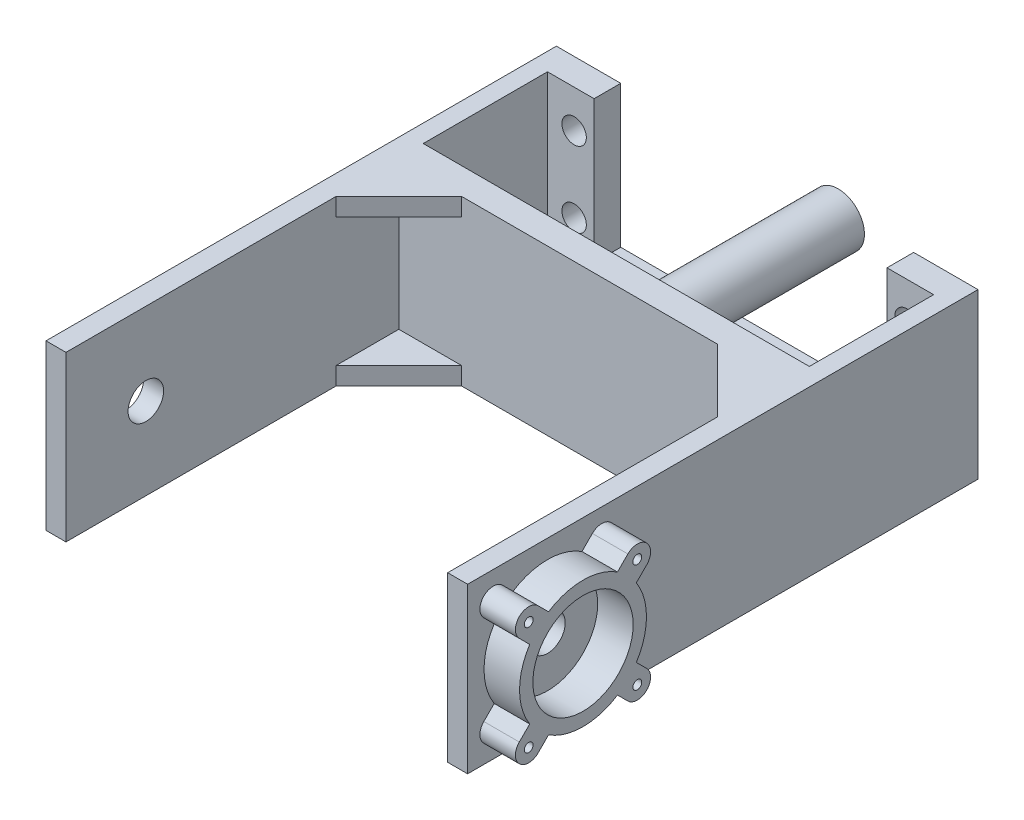
SolidWorks part; units mm, degrees
material "ABS"
ref_plane "Front Plane" through (0, 0, 0) normal (0, 0, 1) x (1, 0, 0)
ref_plane "Top Plane" through (0, 0, 0) normal (0, 1, 0) x (1, 0, 0)
ref_plane "Right Plane" through (0, 0, 0) normal (1, 0, 0) x (0, 0, -1)
sketch "Sketch1" plane through (0, 0, 0) normal (0, 1, 0) x (1, 0, 0)
  line L1 (-47.5, 20) -> (47.5, 20)
  line L2 (-47.5, 20) -> (-47.5, -20)
  line L3 (-47.5, -20) -> (47.5, -20)
  line L4 (47.5, 20) -> (47.5, -20)
  line L5 (-47.5, 20) -> (47.5, -20) construction
  line L6 (-47.5, -20) -> (47.5, 20) construction
  point P0 (0, 0)
  dimension "D1" = 95
  dimension "D2" = 40
extrude "Boss-Extrude1" add sketch "Sketch1" along normal blind 5
sketch "Sketch2" plane through (0, 5, 0) normal (0, 1, 0) x (1, 0, 0)
  line L0 (0, 20) -> (0, -20) construction
  line L1 (-47.5, -20) -> (47.5, -20) construction
  line L2 (-33, 20) -> (-33, -20) construction
  line L3 (47.5, 20) -> (-47.5, 20) construction
  line L4 (-47.5, 20) -> (-47.5, -20) construction
  line L5 (-33, 20) -> (-47.5, 20)
  line L6 (-33, 20) -> (-33, 14)
  line L7 (-33, 14) -> (-47.5, 14)
  line L8 (-47.5, 20) -> (-47.5, 14)
  line L9 (33, 14) -> (47.5, 14)
  line L10 (47.5, 20) -> (47.5, 14)
  line L11 (33, 20) -> (47.5, 20)
  line L12 (33, 20) -> (33, 14)
  point P6 (0, 0)
  dimension "D1" = 33
  dimension "D2" = 6
extrude "Boss-Extrude2" add sketch "Sketch2" along normal blind 32
sketch "Sketch3" plane through (0, 37, 0) normal (0, 1, 0) x (1, 0, 0)
  line L1 (-47.5, 20) -> (47.5, 20)
  line L2 (-47.5, 20) -> (-47.5, 14)
  line L3 (-47.5, 14) -> (47.5, 14)
  line L4 (47.5, 20) -> (47.5, 14)
extrude "Boss-Extrude3" [suppressed] add sketch "Sketch3" against normal blind 6
sketch "Sketch4" plane through (0, 0, -20) normal (0, 0, -1) x (-1, 0, 0)
  line L0 (0, 0) -> (0, 43) construction
  line L2 (-33, 5) -> (33, 5) construction
  circle A0 centre (37.5, 11.5) radius 2.75
  circle A1 centre (37.5, 28.5) radius 2.75
  circle A2 centre (-37.5, 28.5) radius 2.75
  circle A3 centre (-37.5, 11.5) radius 2.75
  dimension "D1" = 5.5
  dimension "D4" = 5.5
  dimension "D2" = 37.5
  dimension "D3" = 17
extrude "Cut-Extrude1" cut sketch "Sketch4" against normal blind 6
sketch "Sketch6" plane through (0, 5, 0) normal (0, 1, 0) x (1, 0, 0)
  line L0 (-47.5, -20) -> (47.5, -20) construction
  line L2 (0, 0) -> (0, -20) construction
  circle A0 centre (-38, 0) radius 2.7
  circle A1 centre (38, 0) radius 2.7
  dimension "D1" = 20
  dimension "D2" = 76
extrude "Cut-Extrude2" [suppressed] cut sketch "Sketch6" against normal blind 6
sketch "Sketch7" plane through (-47.5, 0, 0) normal (-1, 0, 0) x (0, 0, 1)
  line L0 (20, 5) -> (-14, 37)
  line L1 (-14, 37) -> (-14, 5)
  line L2 (-14, 5) -> (20, 5)
extrude "Boss-Extrude4" [suppressed] add sketch "Sketch7" against normal blind 4
mirror "Mirror1" [suppressed] about plane through (0, 0, 0) normal (1, 0, 0)
sketch "Sketch9" [suppressed] plane through (0, 5, 0) normal (0, 1, 0) x (1, 0, 0)
  line L0 (47.5, -20) -> (47.5, 14) construction
  line L1 (-47.5, -20) -> (47.5, -20)
  line L2 (-47.5, -20) -> (-47.5, -14)
  line L3 (-47.5, -14) -> (47.5, -14)
  line L4 (47.5, -20) -> (47.5, -14)
  dimension "D1" = 6
sketch "Sketch10" plane through (0, 5, 0) normal (0, 1, 0) x (1, 0, 0)
  line L0 (47.5, -20) -> (47.5, 14) construction
  line L1 (-47.5, -20) -> (47.5, -20)
  line L2 (-47.5, -20) -> (-47.5, -14)
  line L3 (-43.5, -14) -> (43.5, -14)
  line L4 (47.5, -20) -> (47.5, -19)
  line L5 (-47.5, 14) -> (-33, 14) construction
  line L6 (-47.5, -20) -> (-43.5, -20)
  line L7 (-47.5, -20) -> (-47.5, 14)
  line L8 (-47.5, 14) -> (-43.5, 14)
  line L9 (-43.5, -14) -> (-43.5, 14)
  line L10 (33, 14) -> (47.5, 14) construction
  line L11 (47.5, -20) -> (43.5, -20)
  line L12 (47.5, -20) -> (47.5, 14)
  line L13 (47.5, 14) -> (43.5, 14)
  line L14 (43.5, -14) -> (43.5, 14)
  line M12 (47.5, 14) -> (33, 14)
  line M16 (-33, 14) -> (-47.5, 14)
  line M17 (-47.5, 14) -> (-47.5, -20)
  line M18 (-47.5, -20) -> (47.5, -20)
  line M19 (47.5, -20) -> (47.5, 14)
  dimension "D1" = 6
  dimension "D2" = 4
  dimension "D3" = 4
extrude "Boss-Extrude5" add sketch "Sketch10" along normal blind 32 contours L14 L3 L9 L1 M16 M17 M18 M19 M12
sketch "Sketch11" plane through (0, 0, 20) normal (0, 0, 1) x (1, 0, 0)
  line L0 (0, 0) -> (0, 37) construction
  line L1 (-47.5, 37) -> (47.5, 37) construction
  line L2 (-47.5, 0) -> (47.5, 0) construction
  line L6 (-43, 37) -> (-43, 0)
  line L7 (-43, 0) -> (-47.5, 0)
  line L8 (-47.5, 0) -> (-47.5, 37)
  line L9 (-47.5, 37) -> (-43, 37)
  line L10 (47.5, 0) -> (47.5, 37)
  line L11 (43, 0) -> (47.5, 0)
  line L12 (43, 37) -> (43, 0)
  line L13 (47.5, 37) -> (43, 37)
  dimension "D1" = 43
  dimension "D2" = 4.5
extrude "Boss-Extrude6" add sketch "Sketch11" along normal blind 75
sketch "Sketch12" plane through (-47.5, 0, 0) normal (-1, 0, 0) x (0, 0, 1)
  line L0 (95, 37) -> (95, 0) construction
  circle A0 centre (77, 18.5) radius 4
  dimension "D1" = 18
extrude "Cut-Extrude3" cut sketch "Sketch12" against normal blind 110
sketch "Sketch14" plane through (47.5, 0, 0) normal (1, 0, 0) x (0, 0, -1)
  line L2 (-51.8884, 4.1457) -> (-51.7374, 6.3175)
  line L3 (-47.6457, 8.3884) -> (-50.0959, 10.5765)
  line L6 (-76.3543, 8.3884) -> (-58.0271, -2.1553)
  line L7 (-72.1116, 4.1457) -> (-83.6295, -8.7518)
  line L10 (-72.1116, 32.8543) -> (-56.5863, 37.7326)
  line L11 (-76.3543, 28.6116) -> (-91.7462, 42.3571)
  line L14 (-47.6457, 28.6116) -> (-50.05, 26.266)
  line L15 (-51.8884, 32.8543) -> (-52.5061, 32.1625)
  circle A2 centre (-77, 18.5) radius 25.0466
  arc A3 (-91.7462, 42.3571) -> (-58.0271, -2.1553) centre (-77, 18.5) ccw
  arc A6 (-51.8884, 4.1457) -> (-47.8982, 8.6138) centre (-49.7671, 6.2671) ccw
  circle A7 centre (-49.7671, 6.2671) radius 1
  arc A10 (-76.3543, 8.3884) -> (-71.8862, 4.3982) centre (-74.2329, 6.2671) ccw
  circle A11 centre (-74.2329, 6.2671) radius 1
  arc A14 (-72.1116, 32.8543) -> (-76.1018, 28.3862) centre (-74.2329, 30.7329) ccw
  circle A15 centre (-74.2329, 30.7329) radius 1
  arc A18 (-47.6457, 28.6116) -> (-52.1138, 32.6018) centre (-49.7671, 30.7329) ccw
  circle A19 centre (-49.7671, 30.7329) radius 1
  circle A20 centre (-77, 18.5) radius 28.0466 construction
  arc A21 (-83.6295, -8.7518) -> (-51.7374, 6.3175) centre (-77, 18.5) ccw
  arc A22 (-50.0959, 10.5765) -> (-50.05, 26.266) centre (-77, 18.5) ccw
  arc A23 (-52.5061, 32.1625) -> (-56.5863, 37.7326) centre (-77, 18.5) ccw
  point P64 (-62, 18.5)
  dimension "D1" = 3
extrude "Boss-Extrude8" [suppressed] add sketch "Sketch14" along normal blind 8 contours L15 A23 L10 A14 L11 A3 L6 A10 L7 A21 L2 A6 L3 A22 L14 A18 A2 A7 A11 A15 A19
sketch "Sketch15" plane through (0, 37, 0) normal (0, 1, 0) x (1, 0, 0)
  line L0 (28.8579, -20) -> (43, -34.1421)
  line L1 (-43, -20) -> (43, -20) construction
  line L2 (43, -95) -> (43, -20) construction
  line L3 (0, 0) -> (0, -25.5678) construction
  line L4 (28.8579, -20) -> (43, -20)
  line L5 (43, -20) -> (43, -34.1421)
  line L6 (-28.8579, -20) -> (-43, -20)
  line L7 (-28.8579, -20) -> (-43, -34.1421)
  line L8 (-43, -20) -> (-43, -34.1421)
  dimension "D1" = 20
  dimension "D2" = 45
extrude "Boss-Extrude9" add sketch "Sketch15" against normal blind 4
ref_plane "Plane1" through (0, 18.5, 0) normal (0, 1, 0) x (1, 0, 0)
mirror "Mirror2" about plane through (0, 18.5, 0) normal (0, 1, 0) of "Boss-Extrude9"
sketch "Sketch16" plane through (47.5, 0, 0) normal (1, 0, 0) x (0, 0, -1)
  line L0 (-77, 37) -> (-77, 0) construction
  line L1 (-95, 37) -> (20, 37) construction
  line L2 (-66.8884, 4.1457) -> (-69.2347, 6.4921)
  line L3 (-62.6457, 8.3884) -> (-64.9921, 10.7347)
  line L4 (-95, 0) -> (20, 0) construction
  line L5 (-95, 0) -> (-95, 37) construction
  line L6 (-91.3543, 8.3884) -> (-89.0079, 10.7347)
  line L7 (-87.1116, 4.1457) -> (-84.7653, 6.4921)
  line L8 (-95, 18.5) -> (-53.5634, 18.5) construction
  line L10 (-87.1116, 32.8543) -> (-84.7653, 30.5079)
  line L11 (-91.3543, 28.6116) -> (-89.0079, 26.2653)
  line L14 (-62.6457, 28.6116) -> (-64.9921, 26.2653)
  line L15 (-66.8884, 32.8543) -> (-69.2347, 30.5079)
  circle A0 centre (-77, 18.5) radius 11.3
  arc A1 (-89.0079, 26.2653) -> (-89.0079, 10.7347) centre (-77, 18.5) ccw
  circle A4 centre (-64.7671, 6.2671) radius 1
  arc A5 (-66.8884, 4.1457) -> (-62.6457, 8.3884) centre (-64.7671, 6.2671) ccw
  circle A8 centre (-89.2329, 6.2671) radius 1
  arc A9 (-91.3543, 8.3884) -> (-87.1116, 4.1457) centre (-89.2329, 6.2671) ccw
  circle A12 centre (-89.2329, 30.7329) radius 1
  arc A13 (-87.1116, 32.8543) -> (-91.3543, 28.6116) centre (-89.2329, 30.7329) ccw
  circle A16 centre (-64.7671, 30.7329) radius 1
  arc A17 (-62.6457, 28.6116) -> (-66.8884, 32.8543) centre (-64.7671, 30.7329) ccw
  arc A18 (-69.2347, 30.5079) -> (-84.7653, 30.5079) centre (-77, 18.5) ccw
  arc A19 (-64.9921, 10.7347) -> (-64.9921, 26.2653) centre (-77, 18.5) ccw
  arc A20 (-84.7653, 6.4921) -> (-69.2347, 6.4921) centre (-77, 18.5) ccw
  point P3 (-91.3543, 32.8543)
  point P63 (-77, 18.5)
  dimension "D1" = 22.6
  dimension "D2" = 28.6
  dimension "D3" = 3
  dimension "D4" = 2
  dimension "D5" = 3.3182
  dimension "D6" = 17.3
  dimension "D7" = 20.3
  dimension "D8" = 18
extrude "Boss-Extrude11" add sketch "Sketch16" along normal blind 8
sketch "Sketch17" plane through (0, 0, 14) normal (0, 0, -1) x (-1, 0, 0)
  line L0 (43.5, 37) -> (-43.5, 37) construction
  circle A0 centre (0, 19) radius 5.9121
  dimension "D1" = 18
extrude "Boss-Extrude12" add sketch "Sketch17" along normal blind 50
